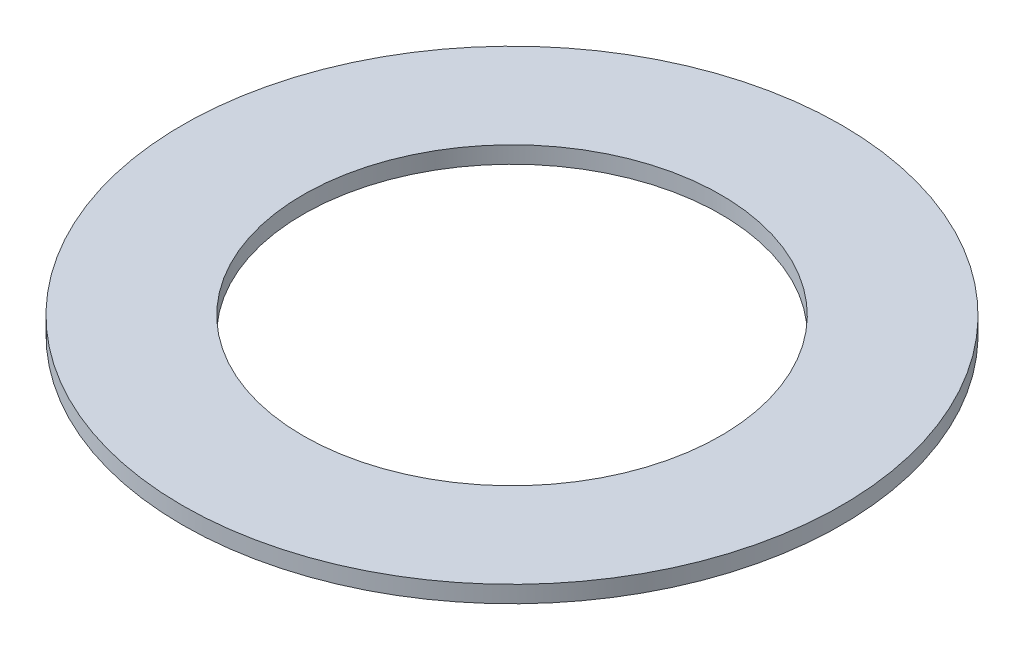
SolidWorks part; units mm, degrees
ref_plane "Front Plane" through (0, 0, 0) normal (0, 0, 1) x (1, 0, 0)
ref_plane "Top Plane" through (0, 0, 0) normal (0, 1, 0) x (1, 0, 0)
ref_plane "Right Plane" through (0, 0, 0) normal (1, 0, 0) x (0, 0, -1)
sketch "Sketch1" plane through (0, 0, 0) normal (0, 1, 0) x (1, 0, 0)
  circle A0 centre (0, 0) radius 78.2
  circle A1 centre (0, 0) radius 49.55
  dimension "D1" = 156.4
  dimension "D2" = 99.1
extrude "Boss-Extrude1" add sketch "Sketch1" along normal blind 4
